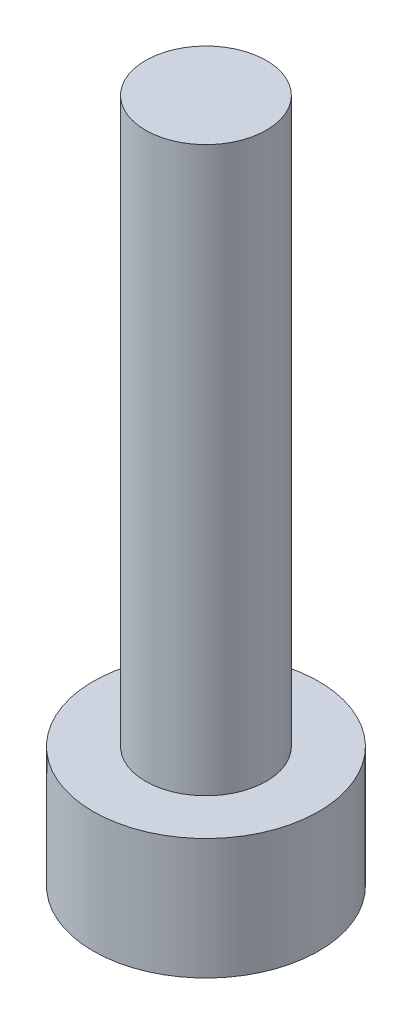
SolidWorks part; units mm, degrees
ref_plane "前视基准面" through (0, 0, 0) normal (0, 0, 1) x (1, 0, 0)
ref_plane "上视基准面" through (0, 0, 0) normal (0, 1, 0) x (1, 0, 0)
ref_plane "右视基准面" through (0, 0, 0) normal (1, 0, 0) x (0, 0, -1)
sketch "草图1" plane through (0, 0, 0) normal (0, 1, 0) x (1, 0, 0)
  circle A0 centre (0, 0) radius 2.8
  dimension "D1" = 5.6
extrude "凸台-拉伸1" add sketch "草图1" along normal blind 3
sketch "草图2" plane through (0, 3, 0) normal (0, 1, 0) x (1, 0, 0)
  circle A0 centre (0, 0) radius 1.5
  dimension "D1" = 3
extrude "凸台-拉伸2" add sketch "草图2" along normal blind 14
